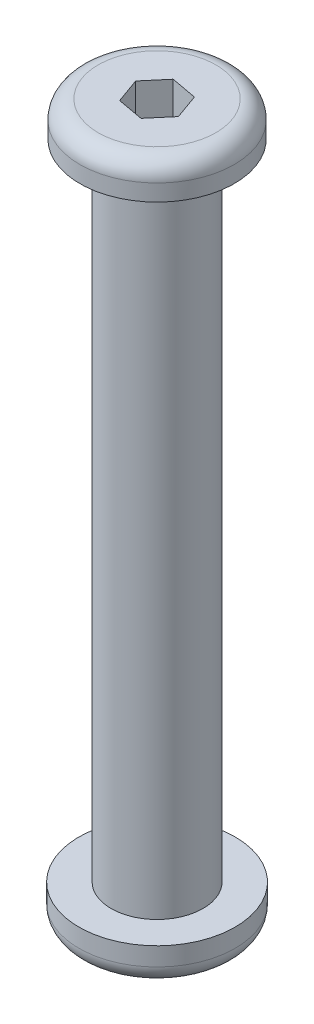
SolidWorks part; units mm, degrees
material "AISI 304"
ref_plane "前视基准面" through (0, 0, 0) normal (0, 0, 1) x (1, 0, 0)
ref_plane "上视基准面" through (0, 0, 0) normal (0, 1, 0) x (1, 0, 0)
ref_plane "右视基准面" through (0, 0, 0) normal (1, 0, 0) x (0, 0, -1)
other "Configuration Table"
sketch "草图1" plane through (0, 0, 0) normal (0, 1, 0) x (1, 0, 0)
  circle A0 centre (0, 0) radius 2.5
  dimension "D1" = 5
extrude "凸台-拉伸1" add sketch "草图1" along normal blind 35
sketch "草图2" plane through (0, 35, 0) normal (0, 1, 0) x (1, 0, 0)
  line L1 (0.9335, 1.1008) -> (-0.4866, 1.3589)
  line L2 (-0.4866, 1.3589) -> (-1.4201, 0.258)
  line L3 (-1.4201, 0.258) -> (-0.9335, -1.1008)
  line L4 (-0.9335, -1.1008) -> (0.4866, -1.3589)
  line L5 (0.4866, -1.3589) -> (1.4201, -0.258)
  line L6 (1.4201, -0.258) -> (0.9335, 1.1008)
  circle A0 centre (0, 0) radius 4.2
  circle A1 centre (0, 0) radius 1.25 construction
  dimension "D1" = 8.4
  dimension "D2" = 2.5
extrude "凸台-拉伸2" add sketch "草图2" along normal blind 1.9
sketch "草图3" plane through (0, 0, 0) normal (0, -1, 0) x (1, 0, 0)
  line L1 (0.8318, 1.1796) -> (-0.6057, 1.3102)
  line L2 (-0.6057, 1.3102) -> (-1.4375, 0.1305)
  line L3 (-1.4375, 0.1305) -> (-0.8318, -1.1796)
  line L4 (-0.8318, -1.1796) -> (0.6057, -1.3102)
  line L5 (0.6057, -1.3102) -> (1.4375, -0.1305)
  line L6 (1.4375, -0.1305) -> (0.8318, 1.1796)
  circle A0 centre (0, 0) radius 4.25
  circle A1 centre (0, 0) radius 1.25 construction
  dimension "D1" = 8.5
  dimension "D2" = 2.5
extrude "凸台-拉伸3" add sketch "草图3" along normal blind 2
fillet "圆角1" radius 1 2 edges at (0, 36.9, 4.2) (0, -2, -4.25)
